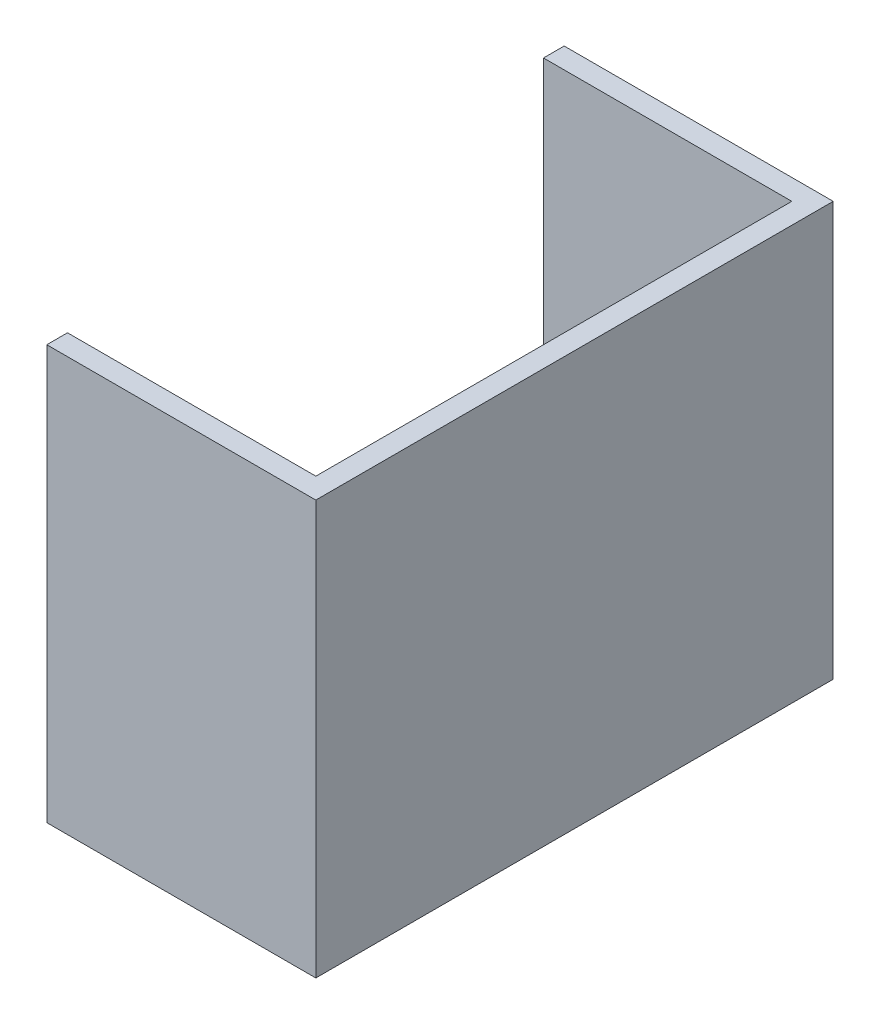
SolidWorks part; units mm, degrees
ref_plane "정면" through (0, 0, 0) normal (0, 0, 1) x (1, 0, 0)
ref_plane "윗면" through (0, 0, 0) normal (0, 1, 0) x (1, 0, 0)
ref_plane "우측면" through (0, 0, 0) normal (1, 0, 0) x (0, 0, -1)
sketch "스케치15" plane through (0, 0, 0) normal (0, 1, 0) x (1, 0, 0)
  line L1 (-6, -12.5) -> (7, -12.5)
  line L2 (-6, -12.5) -> (-6, 12.5)
  line L3 (-6, 12.5) -> (7, 12.5)
  line L4 (7, -12.5) -> (7, 12.5)
  dimension "D1" = 13
  dimension "D2" = 25
extrude "보스-돌출4" add sketch "스케치15" along normal blind 20
sketch "스케치16" plane through (0, 0, 0) normal (0, 1, 0) x (1, 0, 0)
  line L1 (-6, 11.5) -> (6, 11.5)
  line L2 (-6, 11.5) -> (-6, -11.5)
  line L3 (-6, -11.5) -> (6, -11.5)
  line L4 (6, 11.5) -> (6, -11.5)
  line L5 (-6, -12.5) -> (7, -12.5) construction
  line L6 (-6, 12.5) -> (-6, -12.5) construction
  dimension "D1" = 12
  dimension "D2" = 23
  dimension "D3" = 1
extrude "컷-돌출47" cut sketch "스케치16" along normal through all from offset 1
sketch "스케치17" plane through (0, 0, 0) normal (0, 1, 0) x (1, 0, 0)
  line L0 (6, 11.5) -> (-6, 11.5) construction
  line L3 (-6, -3.5) -> (6, -3.5)
  line L4 (-6, -3.5) -> (-6, 5.5)
  line L6 (6, -3.5) -> (6, 5.5)
  arc A0 (6, 5.5) -> (-6, 5.5) centre (0, 5.5) ccw
  dimension "D1" = 12
  dimension "D2" = 12
  dimension "D3" = 9
extrude "컷-돌출48" cut sketch "스케치17" along normal through all
